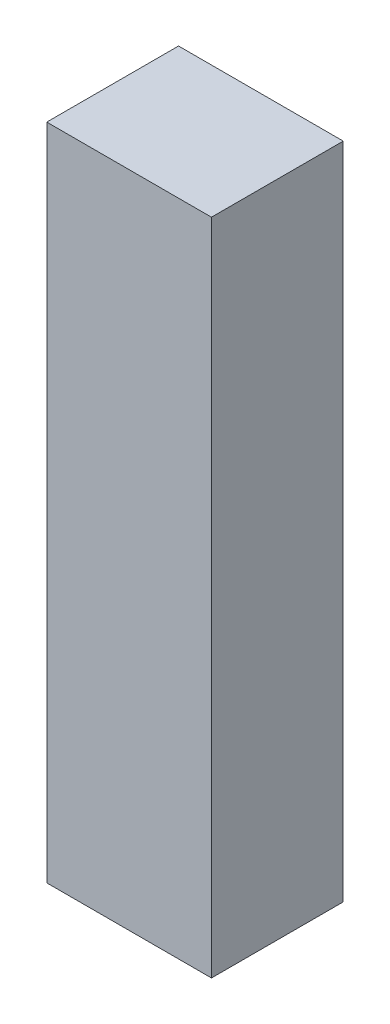
SolidWorks part; units mm, degrees
ref_plane "Front Plane" through (0, 0, 0) normal (0, 0, 1) x (1, 0, 0)
ref_plane "Top Plane" through (0, 0, 0) normal (0, 1, 0) x (1, 0, 0)
ref_plane "Right Plane" through (0, 0, 0) normal (1, 0, 0) x (0, 0, -1)
other "Configuration Table"
sketch "Sketch1" plane through (0, 0, 0) normal (0, 0, 1) x (1, 0, 0)
  line L1 (120, 330) -> (170, 330)
  line L2 (120, 330) -> (120, 530)
  line L3 (120, 530) -> (170, 530)
  line L4 (170, 330) -> (170, 530)
extrude "TOPPING_arka_duvar_pano_surucu_1_1" add sketch "Sketch1" against normal blind 40 from offset 736 separate body
